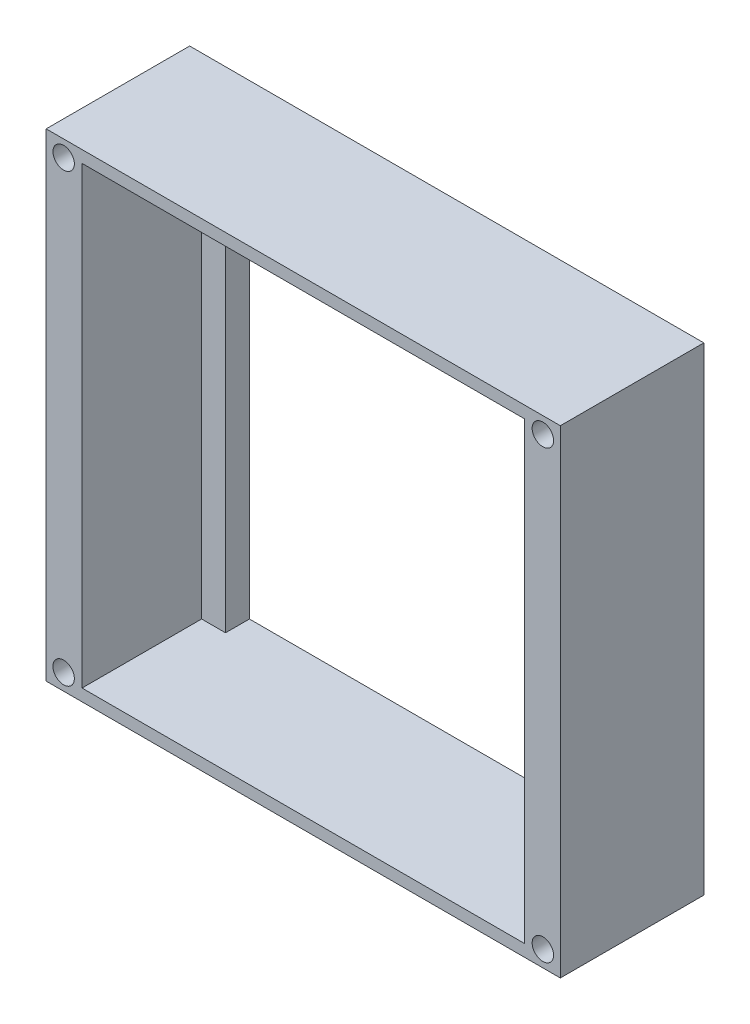
SolidWorks part; units mm, degrees
ref_plane "Front Plane" through (0, 0, 0) normal (0, 0, 1) x (1, 0, 0)
ref_plane "Top Plane" through (0, 0, 0) normal (0, 1, 0) x (1, 0, 0)
ref_plane "Right Plane" through (0, 0, 0) normal (1, 0, 0) x (0, 0, -1)
sketch "Sketch2" plane through (0, 0, 0) normal (0, 0, 1) x (1, 0, 0)
  line L1 (68.2625, -63.5) -> (-68.2625, -63.5)
  line L2 (68.2625, -63.5) -> (68.2625, 63.5)
  line L3 (68.2625, 63.5) -> (-68.2625, 63.5)
  line L4 (-68.2625, -63.5) -> (-68.2625, 63.5)
  line L5 (68.2625, -63.5) -> (-68.2625, 63.5) construction
  line L6 (68.2625, 63.5) -> (-68.2625, -63.5) construction
  line L11 (52.3875, -60.325) -> (-52.3875, 60.325) construction
  line L12 (52.3875, 60.325) -> (-52.3875, -60.325) construction
  point P0 (0, 0)
  point P6 (0, 0)
  point P11 (-63.6206, 59.182)
  point P12 (-63.6206, 59.182)
  point P15 (0, 0)
  point P16 (0, 0)
  point P25 (-63.5886, 59.1522)
  point P26 (0, 0)
sketch "Sketch3" plane through (0, 0, 0) normal (0, 0, 1) x (1, 0, 0)
  line L5 (58.7375, -60.325) -> (-58.7375, -60.325)
  line L6 (58.7375, -60.325) -> (58.7375, 60.325)
  line L7 (58.7375, 60.325) -> (-58.7375, 60.325)
  line L8 (-58.7375, -60.325) -> (-58.7375, 60.325)
  line L9 (58.7375, -60.325) -> (-58.7375, 60.325) construction
  line L10 (58.7375, 60.325) -> (-58.7375, -60.325) construction
  point P0 (0, 0)
extrude "Boss-Extrude1" add sketch "Sketch2" against normal blind 38.1
sketch "Sketch4" plane through (0, 0, -38.1) normal (0, 0, -1) x (-1, 0, 0)
  line L1 (52.3875, -60.325) -> (-52.3875, -60.325)
  line L2 (52.3875, -60.325) -> (52.3875, 60.325)
  line L3 (52.3875, 60.325) -> (-52.3875, 60.325)
  line L4 (-52.3875, -60.325) -> (-52.3875, 60.325)
  line L5 (52.3875, -60.325) -> (-52.3875, 60.325) construction
  line L6 (52.3875, 60.325) -> (-52.3875, -60.325) construction
  point P0 (0, 0)
extrude "Cut-Extrude2" cut sketch "Sketch3" against normal blind 31.75 contours L8 L7 L6 L5
extrude "Cut-Extrude3" cut sketch "Sketch4" against normal blind 38.1 contours L4 L3 L2 L1
sketch "Sketch5" plane through (0, 0, 0) normal (0, 0, 1) x (1, 0, 0)
  circle A0 centre (-63.6206, 59.182) radius 2.8448
  circle A1 centre (63.6206, 59.182) radius 2.8448
  circle A2 centre (63.6206, -59.182) radius 2.8448
  circle A3 centre (-63.6206, -59.182) radius 2.8448
extrude "Cut-Extrude4" cut sketch "Sketch5" against normal blind 25.4
